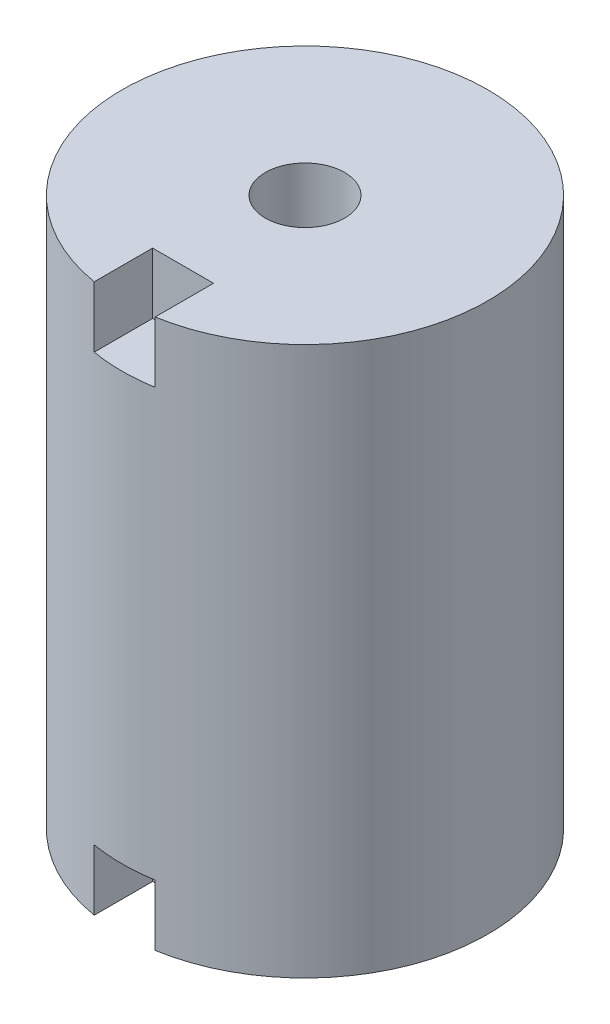
SolidWorks part; units mm, degrees
ref_plane "Plano frontal" through (0, 0, 0) normal (0, 0, 1) x (1, 0, 0)
ref_plane "Plano superior" through (0, 0, 0) normal (0, 1, 0) x (1, 0, 0)
ref_plane "Plano direito" through (0, 0, 0) normal (1, 0, 0) x (0, 0, -1)
sketch "Esboço2" plane through (0, 0, 0) normal (0, 1, 0) x (1, 0, 0)
  circle A0 centre (0, 0) radius 1.3
  circle A1 centre (0, 0) radius 6
  dimension "D1" = 2.6
  dimension "D2" = 12
extrude "Ressalto-extrusão1" add sketch "Esboço2" along normal mid plane 18
sketch "Esboço3" plane through (0, -9, 0) normal (0, -1, 0) x (1, 0, 0)
  line L0 (-3.1052, 2.6) -> (3.1052, 2.6)
  arc A0 (-3.1052, 2.6) -> (3.1052, 2.6) centre (0, 0) ccw
  dimension "D1" = 8.1
  dimension "D2" = 2.6
extrude "Corte-extrusão1" cut sketch "Esboço3" against normal blind 6
sketch "Esboço4" plane through (0, 9, 0) normal (0, 1, 0) x (1, 0, 0)
  line L0 (-1.3, 0) -> (1.3, 0) construction
  line L9 (1, -7) -> (1, -4)
  line L10 (-1, -4) -> (1, -4)
  line L11 (-1, -7) -> (-1, -4)
  line L12 (-1, -7) -> (1, -7)
  circle A0 centre (0, 0) radius 1.3 construction
  dimension "D1" = 4
  dimension "D2" = 1
  dimension "D3" = 1
  dimension "D4" = 3
extrude "Corte-extrusão2" cut sketch "Esboço4" against normal blind 2
mirror "Espelhar1" about plane through (0, 0, 0) normal (0, 1, 0) of "Corte-extrusão2"
